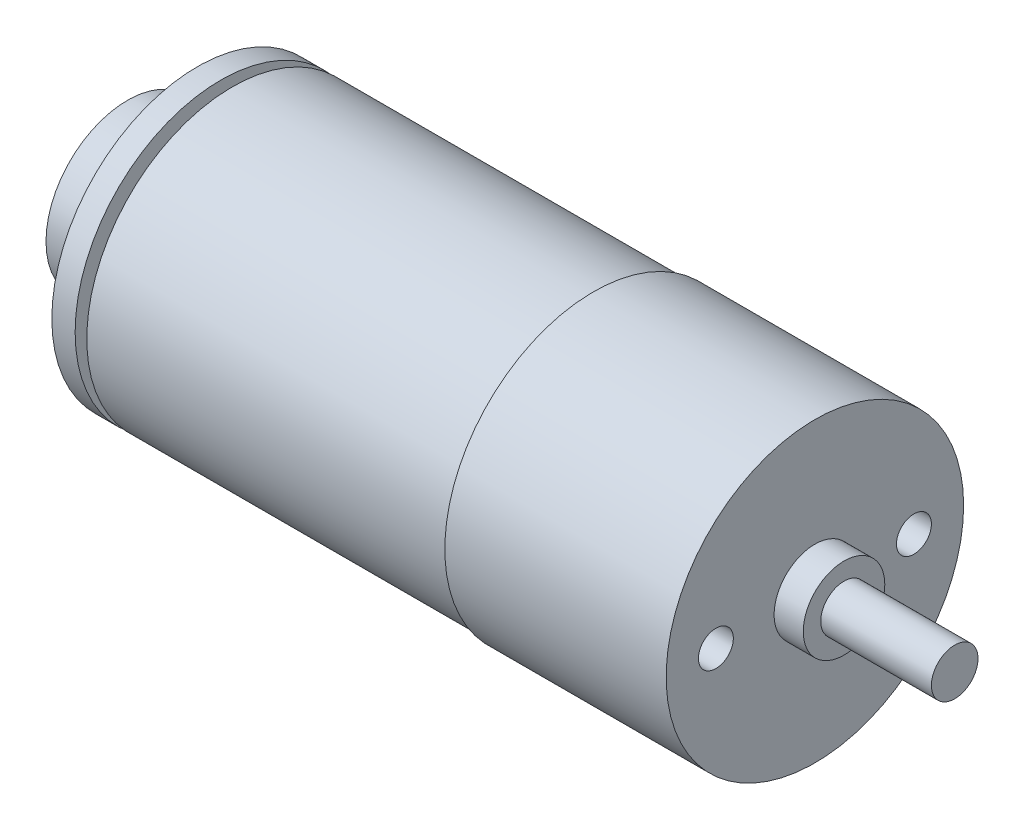
SolidWorks part; units mm, degrees
ref_plane "前视基准面" through (0, 0, 0) normal (0, 0, 1) x (1, 0, 0)
ref_plane "上视基准面" through (0, 0, 0) normal (0, 1, 0) x (1, 0, 0)
ref_plane "右视基准面" through (0, 0, 0) normal (1, 0, 0) x (0, 0, -1)
sketch "草图1" plane through (0, 0, 0) normal (1, 0, 0) x (0, 0, -1)
  circle A0 centre (0, 0) radius 12.5
  dimension "D1" = 25
extrude "凸台-拉伸1" add sketch "草图1" along normal blind 31
sketch "草图2" plane through (31, 0, 0) normal (1, 0, 0) x (0, 0, -1)
  circle A0 centre (0, 0) radius 12.7673
extrude "凸台-拉伸2" add sketch "草图2" along normal blind 19
sketch "草图3" plane through (50, 0, 0) normal (1, 0, 0) x (0, 0, -1)
  circle A0 centre (0, 0) radius 3.5
  dimension "D1" = 7
extrude "凸台-拉伸3" add sketch "草图3" along normal blind 2.5
sketch "草图4" plane through (52.5, 0, 0) normal (1, 0, 0) x (0, 0, -1)
  circle A0 centre (0, 0) radius 2
  dimension "D1" = 4
extrude "凸台-拉伸4" add sketch "草图4" along normal blind 9.5
sketch "草图5" plane through (0, 0, 0) normal (-1, 0, 0) x (0, 0, 1)
  circle A0 centre (0, 0) radius 12.5
extrude "凸台-拉伸5" add sketch "草图5" along normal blind 2 from offset 1 separate body
sketch "草图6" plane through (-3, 0, 0) normal (-1, 0, 0) x (0, 0, 1)
  circle A0 centre (0, 0) radius 1.5799
extrude "凸台-拉伸6" add sketch "草图6" against normal blind 4
sketch "草图7" plane through (-3, 0, 0) normal (-1, 0, 0) x (0, 0, 1)
  circle A0 centre (0, 0) radius 7
  dimension "D1" = 14
extrude "凸台-拉伸7" add sketch "草图7" along normal blind 6
sketch "草图8" plane through (50, 0, 0) normal (1, 0, 0) x (0, 0, -1)
  line L0 (0, 0) -> (8.5, 0) construction
  line L1 (0, 0) -> (0, -10.1151) construction
  circle A0 centre (8.5, 0) radius 1.5
  circle A1 centre (-8.5, 0) radius 1.5
  dimension "D2" = 3
  dimension "D1" = 8.5
extrude "切除-拉伸1" cut sketch "草图8" against normal blind 3
